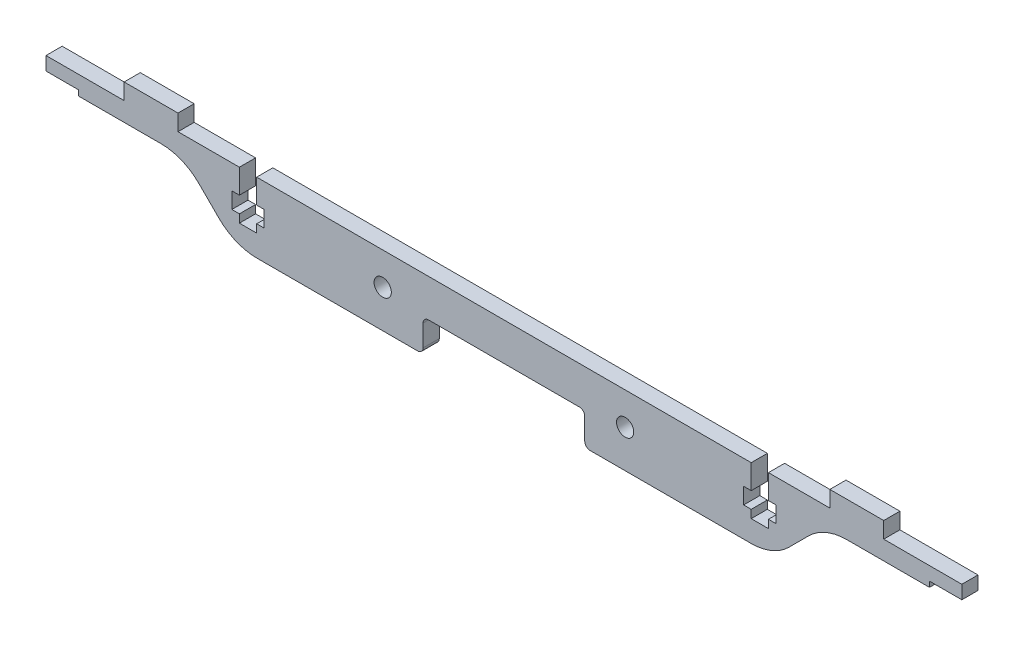
SolidWorks part; units mm, degrees
material "Thornel Mat VMA"
ref_plane "前视基准面" through (0, 0, 0) normal (0, 0, 1) x (1, 0, 0)
ref_plane "上视基准面" through (0, 0, 0) normal (0, 1, 0) x (1, 0, 0)
ref_plane "右视基准面" through (0, 0, 0) normal (1, 0, 0) x (0, 0, -1)
sketch "草图1" plane through (0, 0, 0) normal (0, 0, 1) x (1, 0, 0)
  line L0 (0, 25.2525) -> (0, -19.1002) construction
  line L1 (-29.0692, 0) -> (35.2565, 0) construction
  line L2 (-85, 1) -> (-85, 3.5)
  line L3 (-85, 0) -> (85, 0) construction
  line L4 (-85, 0) -> (-85, 3.5) construction
  line L5 (-85, 3.5) -> (-70.5, 3.5)
  line L6 (85, 0) -> (85, 3.5) construction
  line L7 (-85, 1) -> (-79, 1)
  line L8 (-85, 1) -> (-85, 0) construction
  line L9 (-85, 0) -> (-79, 0) construction
  line L10 (-79, 1) -> (-79, 0)
  line L11 (85, 1) -> (79, 1)
  line L12 (85, 1) -> (85, 0) construction
  line L13 (85, 0) -> (79, 0) construction
  line L14 (79, 1) -> (79, 0)
  line L15 (-79, 0) -> (79, 0)
  line L16 (85, 1) -> (85, 3.5)
  line L17 (-60.5, 3.5) -> (-27.5, 3.5)
  line L18 (-70.5, 6.5) -> (-60.5, 6.5)
  line L19 (-70.5, 6.5) -> (-70.5, 3.5)
  line L21 (-60.5, 6.5) -> (-60.5, 3.5)
  line L22 (-27.5, 6.5) -> (-17.5, 6.5)
  line L23 (-27.5, 6.5) -> (-27.5, 3.5)
  line L25 (-17.5, 6.5) -> (-17.5, 3.5)
  line L27 (17.5, 6.5) -> (17.5, 3.5)
  line L28 (27.5, 6.5) -> (17.5, 6.5)
  line L29 (27.5, 6.5) -> (27.5, 3.5)
  line L31 (60.5, 6.5) -> (60.5, 3.5)
  line L32 (70.5, 6.5) -> (60.5, 6.5)
  line L33 (70.5, 6.5) -> (70.5, 3.5)
  line L34 (-17.5, 3.5) -> (17.5, 3.5)
  line L35 (27.5, 3.5) -> (60.5, 3.5)
  line L36 (70.5, 3.5) -> (85, 3.5)
  point P25 (-65.5, 6.5)
  point P26 (-22.5, 6.5)
  dimension "D1" = 3.5
  dimension "D2" = 170
  dimension "D3" = 2.5
  dimension "D4" = 6
  dimension "D5" = 43
  dimension "D6" = 10
  dimension "D7" = 3
  dimension "D8" = 45
extrude "凸台-拉伸1" add sketch "草图1" along normal blind 3
sketch "草图2" plane through (0, 0, 3) normal (0, 0, 1) x (1, 0, 0)
  line L0 (-27.5, 6.5) -> (-27.5, 3.5) construction
  line L1 (-27.5, 3.5) -> (27.5, 3.5)
  line L2 (-27.5, 3.5) -> (-27.5, 6.5)
  line L3 (-27.5, 6.5) -> (27.5, 6.5)
  line L4 (27.5, 3.5) -> (27.5, 6.5)
extrude "切除-拉伸1" cut sketch "草图2" against normal through all
sketch "草图3" plane through (0, 0, 3) normal (0, 0, 1) x (1, 0, 0)
  line L0 (0, 19.4184) -> (0, -21.5993) construction
  line L1 (-79, 0) -> (79, 0) construction
  line L2 (-50, 0) -> (50, 0)
  line L3 (-50, 0) -> (-50, -9.5) construction
  line L4 (-50, -9.5) -> (50, -9.5)
  line L5 (50, 0) -> (50, -9.5) construction
  line L6 (60.5, 3.5) -> (-60.5, 3.5) construction
  line L7 (-50, -9.5) -> (-59.5, 0)
  line L8 (-59.5, 0) -> (-50, 0)
  line L9 (50, -9.5) -> (59.5, 0)
  line L10 (59.5, 0) -> (50, 0)
  dimension "D1" = 13
  dimension "D2" = 100
  dimension "D3" = 45
extrude "凸台-拉伸2" add sketch "草图3" against normal up to surface (3 mm away) up to face at (0, 3.1875, 0)
fillet "圆角1" radius 10 4 edges at (59.5, 0, 1.5) (-59.5, 0, 1.5) (50, -9.5, 1.5) (-50, -9.5, 1.5)
sketch "草图4" plane through (0, 0, 3) normal (0, 0, 1) x (1, 0, 0)
  line L0 (0, 13.4553) -> (0, -23.078) construction
  line L1 (60.5, 3.5) -> (-60.5, 3.5) construction
  line L2 (-49.1, 3.5) -> (-45.9, 3.5)
  line L3 (-49.1, 3.5) -> (-49.1, -1)
  line L4 (-49.1, -5.5) -> (-45.9, -5.5)
  line L5 (-45.9, 3.5) -> (-45.9, -1)
  line L6 (-47.5, 3.5) -> (-47.5, -5.5) construction
  line L7 (-50.5, -1) -> (-49.1, -1)
  line L8 (-50.5, -1) -> (-50.5, -4)
  line L9 (-50.5, -4) -> (-49.1, -4)
  line L10 (-44.5, -1) -> (-44.5, -4)
  line L11 (-60.5, 6.5) -> (-70.5, 6.5) construction
  line L12 (-45.9, -1) -> (-44.5, -1)
  line L13 (-45.9, -4) -> (-45.9, -5.5)
  line L14 (-45.9, -4) -> (-44.5, -4)
  line L15 (-49.1, -4) -> (-49.1, -5.5)
  line L16 (50.5, -1) -> (49.1, -1)
  line L17 (49.1, 3.5) -> (49.1, -1)
  line L18 (49.1, 3.5) -> (45.9, 3.5)
  line L19 (45.9, 3.5) -> (45.9, -1)
  line L20 (45.9, -1) -> (44.5, -1)
  line L21 (44.5, -1) -> (44.5, -4)
  line L22 (45.9, -4) -> (44.5, -4)
  line L23 (45.9, -4) -> (45.9, -5.5)
  line L24 (49.1, -5.5) -> (45.9, -5.5)
  line L25 (49.1, -4) -> (49.1, -5.5)
  line L26 (50.5, -4) -> (49.1, -4)
  line L27 (50.5, -1) -> (50.5, -4)
  line L28 (-45.8579, -9.5) -> (45.8579, -9.5) construction
  line L30 (-15, -9.5) -> (15, -9.5)
  line L31 (-15, -9.5) -> (-15, -3.5)
  line L32 (-15, -3.5) -> (15, -3.5)
  line L33 (15, -9.5) -> (15, -3.5)
  circle A0 centre (-22.5, -2.5) radius 1.6
  circle A1 centre (22.5, -2.5) radius 1.6
  dimension "D7" = 7
  dimension "D8" = 45
  dimension "D9" = 3.2
  dimension "D1" = 12
  dimension "D2" = 3
  dimension "D3" = 6
  dimension "D4" = 4.5
  dimension "D5" = 3.2
  dimension "D6" = 95
  dimension "D10" = 30
  dimension "D11" = 6
extrude "切除-拉伸2" cut sketch "草图4" against normal through all
fillet "圆角2" radius 1 4 edges at (15, -9.5, 1.5) (15, -3.5, 1.5) (-15, -9.5, 1.5) (-15, -3.5, 1.5)
